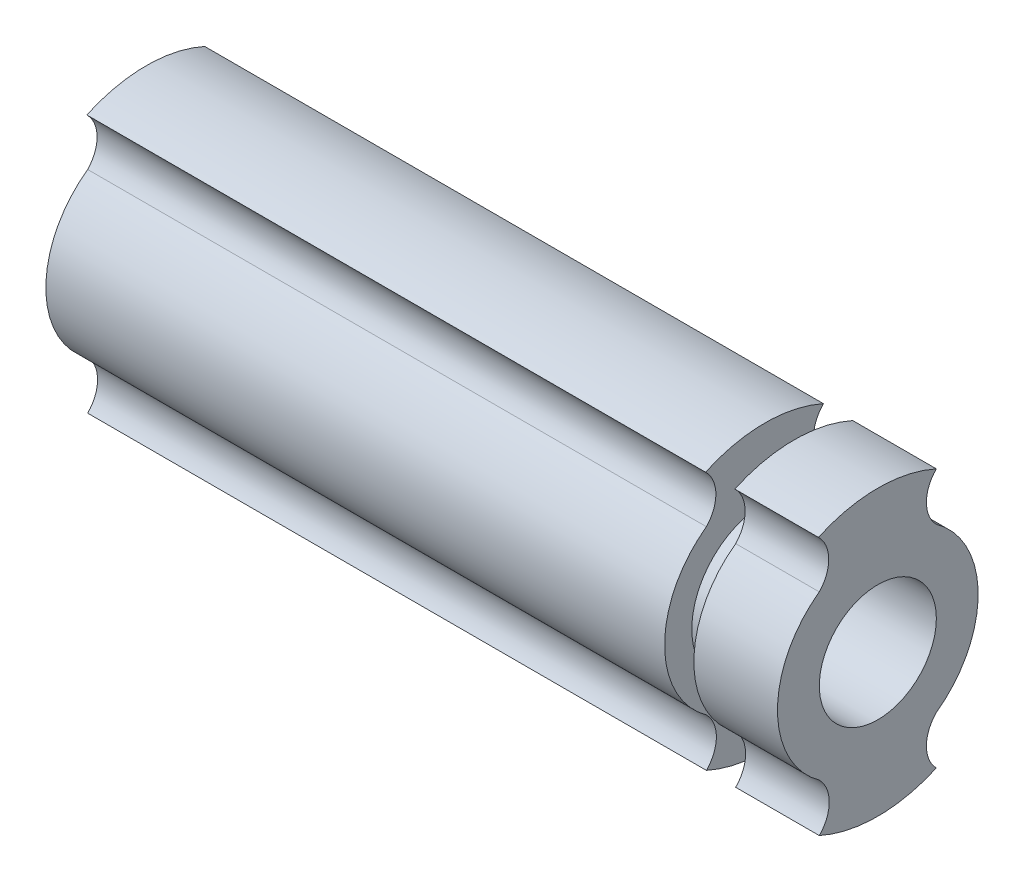
SolidWorks part; units mm, degrees
ref_plane "Front Plane" through (0, 0, 0) normal (0, 0, 1) x (1, 0, 0)
ref_plane "Top Plane" through (0, 0, 0) normal (0, 1, 0) x (1, 0, 0)
ref_plane "Right Plane" through (0, 0, 0) normal (1, 0, 0) x (0, 0, -1)
sketch "Sketch1" plane through (0, 0, 0) normal (1, 0, 0) x (0, 0, -1)
  line L12 (-14, 30.6894) -> (-14, 30.9839) construction
  circle A0 centre (0, 0) radius 14
  arc A1 (-14, 19.4936) -> (-14, -19.4936) centre (0, 0) ccw
  arc A2 (-14, -30.9839) -> (14, -30.9839) centre (0, 0) ccw
  arc A3 (14, 19.4936) -> (14, 30.9839) centre (19.7451, 25.2387) cw
  arc A4 (-14, 19.4936) -> (-14.2023, 30.8917) centre (-19.8002, 25.0915) ccw
  arc A5 (14, -19.4936) -> (14, -30.9839) centre (19.7451, -25.2387) ccw
  arc A6 (-14, -19.4936) -> (-14, -30.9839) centre (-19.7451, -25.2387) cw
  arc A7 (14, 30.9839) -> (-14.2023, 30.8917) centre (0, 0) ccw
  arc A8 (14, -19.4936) -> (14, 19.4936) centre (0, 0) ccw
  dimension "D1" = 28
  dimension "D2" = 24
  dimension "D3" = 34
extrude "Boss-Extrude1" add sketch "Sketch1" along normal blind 175
sketch3d "3DSketch1"
  point P0 (160.1603, 40.9835, 0)
ref_axis "Axis1" through (175, 0, 0) along (-1, 0, 0)
ref_plane "Plane1" through (0, 0, 0) normal (0, 0, -1) x (-1, 0, 0)
sketch "Sketch5" plane through (0, 0, 0) normal (0, 0, 1) x (1, 0, 0)
  line L0 (175, 19.4936) -> (175, 30.8917) construction
  line L1 (148, 41.3803) -> (155, 41.3803)
  line L2 (148, 41.3803) -> (148, 17.5)
  line L3 (148, 17.5) -> (155, 17.5)
  line L4 (155, 41.3803) -> (155, 17.5)
  line L5 (175, 0) -> (0, 0) construction
  dimension "D1" = 20
  dimension "D2" = 17.5
  dimension "D3" = 7
revolve "Cut-Revolve1" cut sketch "Sketch5" angle 360 about axis through (175, 0, 0) along (-1, 0, 0)
